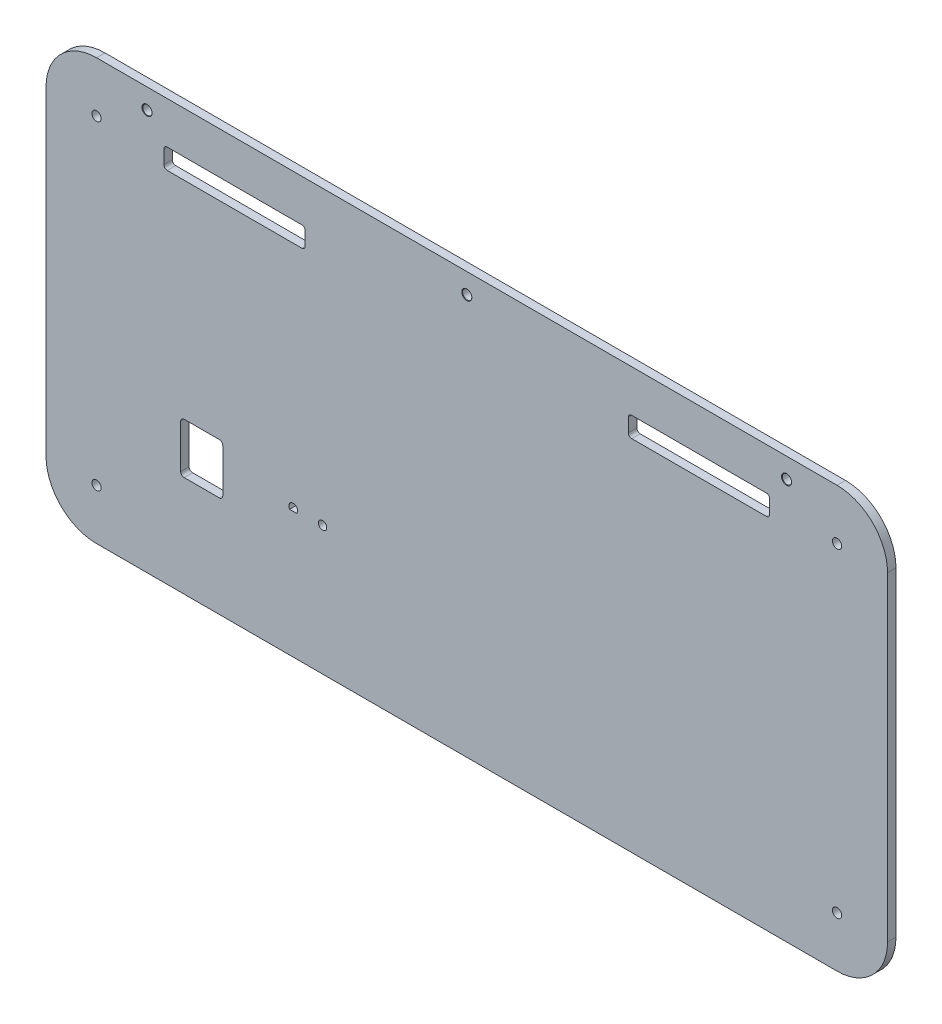
SolidWorks part; units mm, degrees
ref_plane "Plan de face" through (0, 0, 0) normal (0, 0, 1) x (1, 0, 0)
ref_plane "Plan de dessus" through (0, 0, 0) normal (0, 1, 0) x (1, 0, 0)
ref_plane "Plan de droite" through (0, 0, 0) normal (1, 0, 0) x (0, 0, -1)
sketch "Esquisse1" plane through (0, 0, 0) normal (0, 0, 1) x (1, 0, 0)
  line L1 (30, 0) -> (470, 0)
  line L2 (0, 30) -> (0, 220)
  line L3 (30, 250) -> (470, 250)
  line L4 (500, 30) -> (500, 220)
  arc A0 (470, 0) -> (500, 30) centre (470, 30) ccw
  arc A1 (30, 0) -> (0, 30) centre (30, 30) cw
  arc A2 (0, 220) -> (30, 250) centre (30, 220) cw
  arc A3 (500, 220) -> (470, 250) centre (470, 220) ccw
  point P9 (0, 0)
  point P12 (0, 250)
  point P15 (500, 250)
  dimension "D3" = 30
  dimension "D1" = 250
  dimension "D2" = 500
extrude "Boss.-Extru.1" add sketch "Esquisse1" along normal blind 5
hole_wizard "Dégagement M51" positions "Esquisse5" profile "Esquisse6" hole size "M5" standard "ISO" end condition through all
sketch "Esquisse5" plane through (0, 0, 0) normal (0, 0, -1) x (-1, 0, 0)
  line L0 (-500, 30) -> (-500, 220) construction
  line L1 (-470, 250) -> (-30, 250) construction
  line L2 (-30, 0) -> (-470, 0) construction
  line L4 (0, 220) -> (0, 30) construction
  point P0 (-470, 220)
  point P2 (-470, 30)
  point P4 (-30, 30)
  point P6 (-30, 220)
  dimension "D1" = 30
  dimension "D2" = 30
  dimension "D3" = 30
  dimension "D4" = 30
  dimension "D5" = 30
  dimension "D6" = 30
  dimension "D7" = 30
  dimension "D8" = 30
sketch "Esquisse6" plane through (470, 220, 0) normal (1, 0, 0) x (0, 1, 0)
  line L0 (0, 0) -> (0, 5)
  line L1 (0, 5) -> (2.75, 5)
  line L2 (2.75, 5) -> (2.75, 0.025)
  line L3 (2.75, 0.025) -> (2.775, 0)
  line L5 (2.775, 0) -> (0, 0)
  line L6 (-2.75, 0.025) -> (-2.775, 0) construction
  line L11 (0, -6.35) -> (0, 107.95) construction
  dimension "Diamètre du perçage jusqu'au prochain" = 5.5
  dimension "Profondeur du perçage jusqu'au prochain" = 5
  dimension "Diamètre du fraisage entrant" = 5.55
  dimension "Angle du fraisage entrant" = 90
sketch "Esquisse8" plane through (0, 0, 5) normal (0, 0, 1) x (1, 0, 0)
  line L0 (0, 220) -> (0, 30) construction
  line L1 (72, 225) -> (152, 225)
  line L2 (70, 223) -> (70, 215)
  line L3 (72, 213) -> (152, 213)
  line L4 (154, 223) -> (154, 215)
  line L5 (470, 250) -> (30, 250) construction
  line L6 (250, 250) -> (250, 0) construction
  line L7 (30, 0) -> (470, 0) construction
  line L8 (346, 223) -> (346, 215)
  line L9 (428, 213) -> (348, 213)
  line L10 (430, 223) -> (430, 215)
  line L11 (428, 225) -> (348, 225)
  arc A0 (152, 213) -> (154, 215) centre (152, 215) ccw
  arc A1 (70, 215) -> (72, 213) centre (72, 215) ccw
  arc A2 (72, 225) -> (70, 223) centre (72, 223) ccw
  arc A3 (154, 223) -> (152, 225) centre (152, 223) ccw
  arc A4 (346, 223) -> (348, 225) centre (348, 223) cw
  arc A5 (428, 225) -> (430, 223) centre (428, 223) cw
  arc A6 (430, 215) -> (428, 213) centre (428, 215) cw
  arc A7 (348, 213) -> (346, 215) centre (348, 215) cw
  dimension "D1" = 2
  dimension "D2" = 70
  dimension "D3" = 25
  dimension "D4" = 80
  dimension "D5" = 8
extrude "Enlèv. mat.-Extru.1" cut sketch "Esquisse8" against normal through all
hole_wizard "Dégagement M52" positions "Esquisse10" profile "Esquisse11" hole size "M5" standard "ISO" end condition through all
sketch "Esquisse10" plane through (0, 0, 5) normal (0, 0, 1) x (1, 0, 0)
  line L0 (0, 220) -> (0, 30) construction
  line L1 (500, 30) -> (500, 220) construction
  line L2 (470, 250) -> (30, 250) construction
  point P0 (60, 238)
  point P2 (440, 238)
  point P11 (250, 238)
  dimension "D1" = 60
  dimension "D2" = 60
  dimension "D3" = 12
  dimension "D4" = 12
  dimension "D5" = 190
sketch "Esquisse11" plane through (60, 238, 5) normal (1, 0, 0) x (0, -1, 0)
  line L0 (0, 0) -> (0, 5)
  line L1 (0, 5) -> (2.75, 5)
  line L2 (2.75, 5) -> (2.75, 0.25)
  line L3 (2.75, 0.25) -> (3, 0)
  line L5 (3, 0) -> (0, 0)
  line L6 (-2.75, 0.25) -> (-3, 0) construction
  line L11 (0, -6.35) -> (0, 107.95) construction
  dimension "Diamètre du perçage jusqu'au prochain" = 5.5
  dimension "Profondeur du perçage jusqu'au prochain" = 5
  dimension "Diamètre du fraisage entrant" = 6
  dimension "Angle du fraisage entrant" = 90
sketch "Esquisse13" plane through (0, 0, 0) normal (0, 0, -1) x (-1, 0, 0)
  line L5 (-30, 0) -> (-470, 0) construction
  line L6 (-250, 250) -> (-250, 0) construction
  line L7 (-470, 250) -> (-30, 250) construction
  line L8 (-105, 88) -> (-105, 62)
  line L9 (-82, 60) -> (-103, 60)
  line L10 (-80, 88) -> (-80, 62)
  line L11 (-82, 90) -> (-103, 90)
  arc A0 (-82, 60) -> (-80, 62) centre (-82, 62) ccw
  arc A1 (-103, 60) -> (-105, 62) centre (-103, 62) cw
  arc A2 (-105, 88) -> (-103, 90) centre (-103, 88) cw
  arc A3 (-80, 88) -> (-82, 90) centre (-82, 88) ccw
  dimension "D1" = 2
extrude "Enlèv. mat.-Extru.2" cut sketch "Esquisse13" against normal through all
sketch "Esquisse14" plane through (0, 0, 5) normal (0, 0, 1) x (1, 0, 0)
  line L2 (144.7426, 75) -> (148.9526, 75)
  arc A0 (144.7426, 75) -> (148.9526, 75) centre (146.8476, 76.5599) cw
  dimension "D2" = 2.62
  dimension "D1" = 4.21
extrude "Enlèv. mat.-Extru.3" cut sketch "Esquisse14" against normal through all
sketch "Esquisse15" plane through (0, 0, 5) normal (0, 0, 1) x (1, 0, 0)
  circle A0 centre (164.2924, 76.5599) radius 2.5
  dimension "D1" = 5
extrude "Enlèv. mat.-Extru.4" cut sketch "Esquisse15" against normal through all
